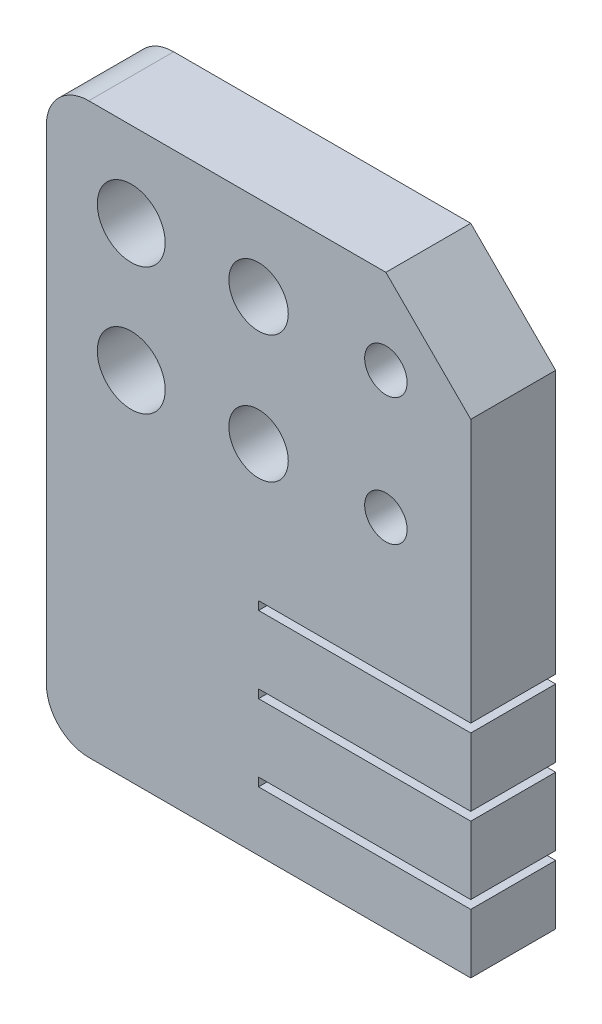
SolidWorks part; units mm, degrees
ref_plane "Front Plane" through (0, 0, 0) normal (0, 0, 1) x (1, 0, 0)
ref_plane "Top Plane" through (0, 0, 0) normal (0, 1, 0) x (1, 0, 0)
ref_plane "Right Plane" through (0, 0, 0) normal (1, 0, 0) x (0, 0, -1)
sketch "Sketch1" plane through (0, 0, 0) normal (0, 0, 1) x (1, 0, 0)
  line L0 (40, 67) -> (50, 57)
  line L1 (5, 0) -> (50, 0)
  line L2 (0, 5) -> (0, 62)
  line L3 (5, 67) -> (40, 67)
  line L4 (50, 0) -> (50, 57)
  line L5 (0, 0) -> (50, 67) construction
  line L6 (0, 67) -> (50, 0) construction
  arc A0 (0, 62) -> (5, 67) centre (5, 62) cw
  arc A1 (5, 0) -> (0, 5) centre (5, 5) cw
  circle A2 centre (10, 57) radius 4
  circle A3 centre (25, 57) radius 3.5
  circle A4 centre (40, 57) radius 2.5
  circle A5 centre (10, 42) radius 4
  circle A6 centre (25, 42) radius 3.5
  circle A7 centre (40, 42) radius 2.5
  point P4 (25, 33.5)
  point P26 (0, 0)
  dimension "D5" = 5
  dimension "D6" = 5
  dimension "D9" = 8
  dimension "D10" = 7
  dimension "D11" = 5
  dimension "D16" = 8
  dimension "D17" = 7
  dimension "D18" = 5
  dimension "D1" = 67
  dimension "D2" = 50
  dimension "D3" = 10
  dimension "D4" = 45
  dimension "D7" = 10
  dimension "D8" = 10
  dimension "D12" = 10
  dimension "D13" = 10
  dimension "D14" = 10
  dimension "D15" = 25
  dimension "D19" = 10
  dimension "D20" = 25
  dimension "D21" = 25
  dimension "D22" = 25
  dimension "D23" = 10
  dimension "D24" = 25
extrude "Boss-Extrude1" add sketch "Sketch1" along normal blind 10
sketch "Sketch2" plane through (0, 0, 10) normal (0, 0, 1) x (1, 0, 0)
  line L0 (50, 26) -> (25, 26)
  line L1 (50, 0) -> (50, 57) construction
  line L2 (25, 26) -> (25, 25)
  line L3 (25, 25) -> (50, 25)
  line L4 (50, 0) -> (50, 57) construction
  line L5 (50, 25) -> (50, 26)
  line L6 (50, 17) -> (25, 17)
  line L7 (25, 17) -> (25, 16)
  line L8 (25, 16) -> (50, 16)
  line L9 (50, 16) -> (50, 17)
  line L10 (50, 8) -> (25, 8)
  line L11 (25, 8) -> (25, 7)
  line L12 (25, 7) -> (50, 7)
  line L13 (50, 7) -> (50, 8)
  line L14 (5, 0) -> (50, 0) construction
  dimension "D1" = 25
  dimension "D2" = 25
  dimension "D3" = 25
  dimension "D4" = 7
  dimension "D5" = 8
  dimension "D6" = 8
  dimension "D7" = 1
  dimension "D8" = 1
  dimension "D9" = 1
extrude "Cut-Extrude1" cut sketch "Sketch2" against normal up to surface (10 mm away) up to face at (28.5, 42, 0)
